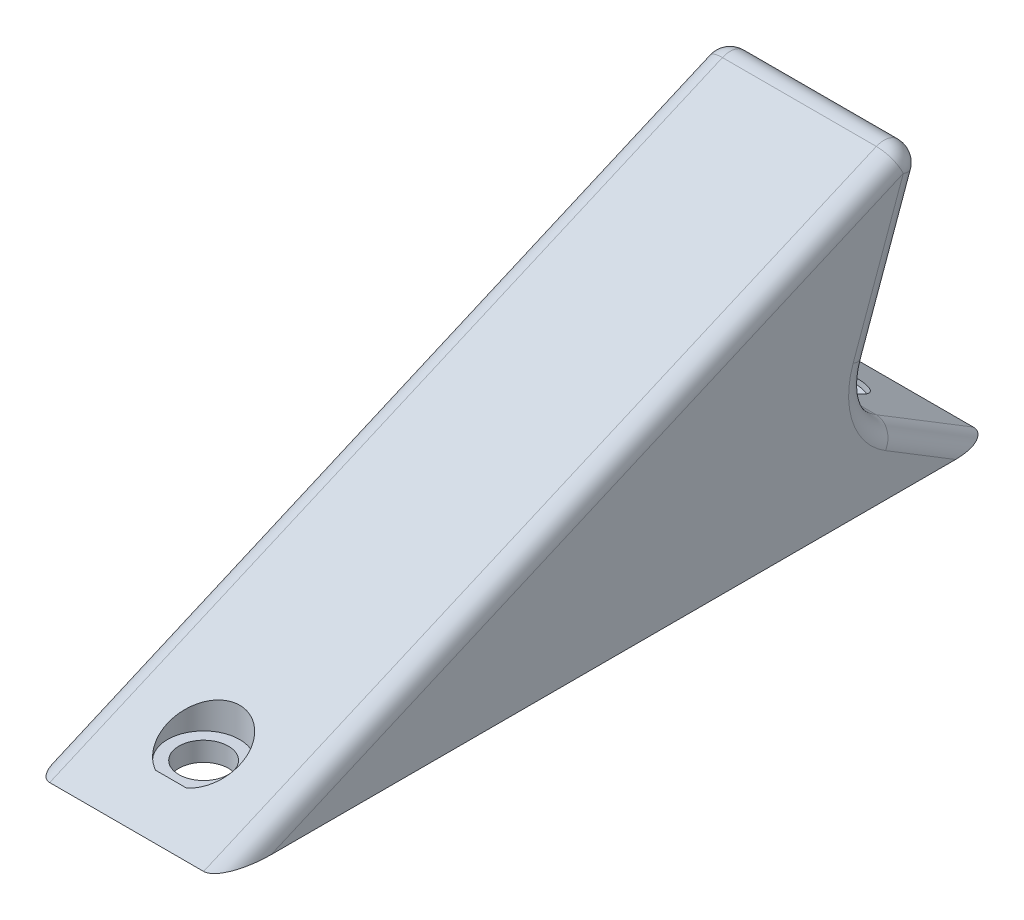
SolidWorks part; units mm, degrees
material "Markforged Onyx"
ref_plane "Front Plane" through (0, 0, 0) normal (0, 0, 1) x (1, 0, 0)
ref_plane "Top Plane" through (0, 0, 0) normal (0, 1, 0) x (1, 0, 0)
ref_plane "Right Plane" through (0, 0, 0) normal (1, 0, 0) x (0, 0, -1)
sketch "Sketch1" plane through (0, 0, 0) normal (1, 0, 0) x (0, 0, -1)
  line L0 (-50.8, 0) -> (50.8, 0) construction
  line L3 (-50.8, 0) -> (50.8, 0)
  line L4 (-50.8, 0) -> (43.3909, 40.8118)
  line L5 (43.3909, 40.8118) -> (32.681, 11.0507)
  line L6 (32.681, 11.0507) -> (50.8, 0)
  dimension "D1" = 101.6
extrude "Boss-Extrude1" add sketch "Sketch1" along normal blind 25.4
fillet "Fillet4" radius 7.62 1 edges at (12.7, 11.0507, -32.681)
fillet "Fillet5" radius 2.54 1 edges at (12.7, 40.8118, -43.3909)
fillet "Fillet6" radius 2.54 10 edges at (0, 3.907, -44.394) (0, 11.7866, -34.769) (0, 26.0931, -38.0942) (0, 37.9987, -40.7508) (25.4, 3.907, -44.394) (25.4, 11.7866, -34.769) (25.4, 26.0931, -38.0942) (25.4, 37.9987, -40.7508) (0, 19.2386, 6.3986) (25.4, 19.2386, 6.3986)
sketch "Sketch2" plane through (0, 0, 0) normal (0, -1, 0) x (1, 0, 0)
  line L0 (12.7, 50.8) -> (12.7, -50.8) construction
  line L1 (22.86, 50.8) -> (2.54, 50.8) construction
  line L2 (22.86, -50.8) -> (2.54, -50.8) construction
  circle A0 centre (12.7, 40.64) radius 3.2639
  circle A1 centre (12.7, -40.64) radius 3.2639
  dimension "D1" = 6.5278
  dimension "D2" = 10.16
  dimension "D3" = 10.16
extrude "Cut-Extrude1" cut sketch "Sketch2" against normal blind 10.16
ref_plane "Plane1" through (0, 2.54, 0) normal (0, -1, 0) x (-1, 0, 0)
sketch "Sketch3" plane through (0, 2.54, 0) normal (0, -1, 0) x (-1, 0, 0)
  circle A0 centre (-12.7, -40.64) radius 4.7625
  circle A1 centre (-12.7, 40.64) radius 4.7625
  dimension "D1" = 9.525
  dimension "D2" = 9.525
extrude "Cut-Extrude4" cut sketch "Sketch3" against normal blind 10.16
